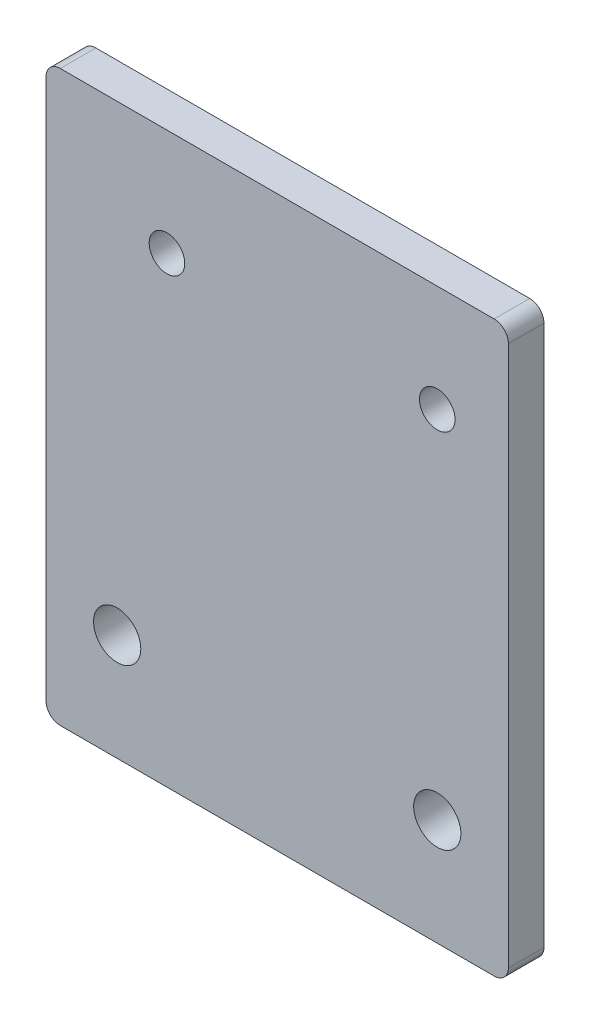
SolidWorks part; units mm, degrees
material "Acrylic (Medium-high impact)"
ref_plane "Front Plane" through (0, 0, 0) normal (0, 0, 1) x (1, 0, 0)
ref_plane "Top Plane" through (0, 0, 0) normal (0, 1, 0) x (1, 0, 0)
ref_plane "Right Plane" through (0, 0, 0) normal (1, 0, 0) x (0, 0, -1)
sketch "Sketch1" plane through (0, 0, 0) normal (0, 0, 1) x (1, 0, 0)
  line L1 (-41.275, -50.8) -> (41.275, -50.8)
  line L2 (-41.275, -50.8) -> (-41.275, 50.8)
  line L3 (-41.275, 50.8) -> (41.275, 50.8)
  line L4 (41.275, -50.8) -> (41.275, 50.8)
  line L5 (-41.275, -50.8) -> (41.275, 50.8) construction
  line L6 (-41.275, 50.8) -> (41.275, -50.8) construction
  point P0 (0, 0)
  dimension "D1" = 82.55
  dimension "D2" = 101.6
extrude "Boss-Extrude1" add sketch "Sketch1" along normal mid plane 6.35
sketch "Sketch2" plane through (0, 0, 3.175) normal (0, 0, 1) x (1, 0, 0)
  line L0 (41.275, -50.8) -> (41.275, 50.8) construction
  line L1 (-28.575, -31.75) -> (28.575, -31.75) construction
  line L2 (-28.575, -31.75) -> (-28.575, 31.75) construction
  line L3 (-28.575, 31.75) -> (28.575, 31.75) construction
  line L4 (28.575, -31.75) -> (28.575, 31.75) construction
  line L5 (-28.575, -31.75) -> (28.575, 31.75) construction
  line L6 (-28.575, 31.75) -> (28.575, -31.75) construction
  line L7 (41.275, 50.8) -> (-41.275, 50.8) construction
  line L8 (-41.275, 50.8) -> (-41.275, -50.8) construction
  circle A0 centre (-19.685, 31.75) radius 3.175
  circle A2 centre (28.575, -31.75) radius 4.2164
  circle A3 centre (-28.575, -31.75) radius 4.2164
  circle A5 centre (28.575, 31.75) radius 3.175
  dimension "D1" = 12.7
  dimension "D2" = 19.05
  dimension "D5" = 8.4328
  dimension "D6" = 6.35
  dimension "D3" = 82.55
  dimension "D4" = 12.7
  dimension "D7" = 8.89
extrude "Cut-Extrude1" cut sketch "Sketch2" against normal through all
fillet "Fillet1" radius 2.54 4 edges at (-41.275, -50.8, 0) (41.275, -50.8, 0) (41.275, 50.8, 0) (-41.275, 50.8, 0)
